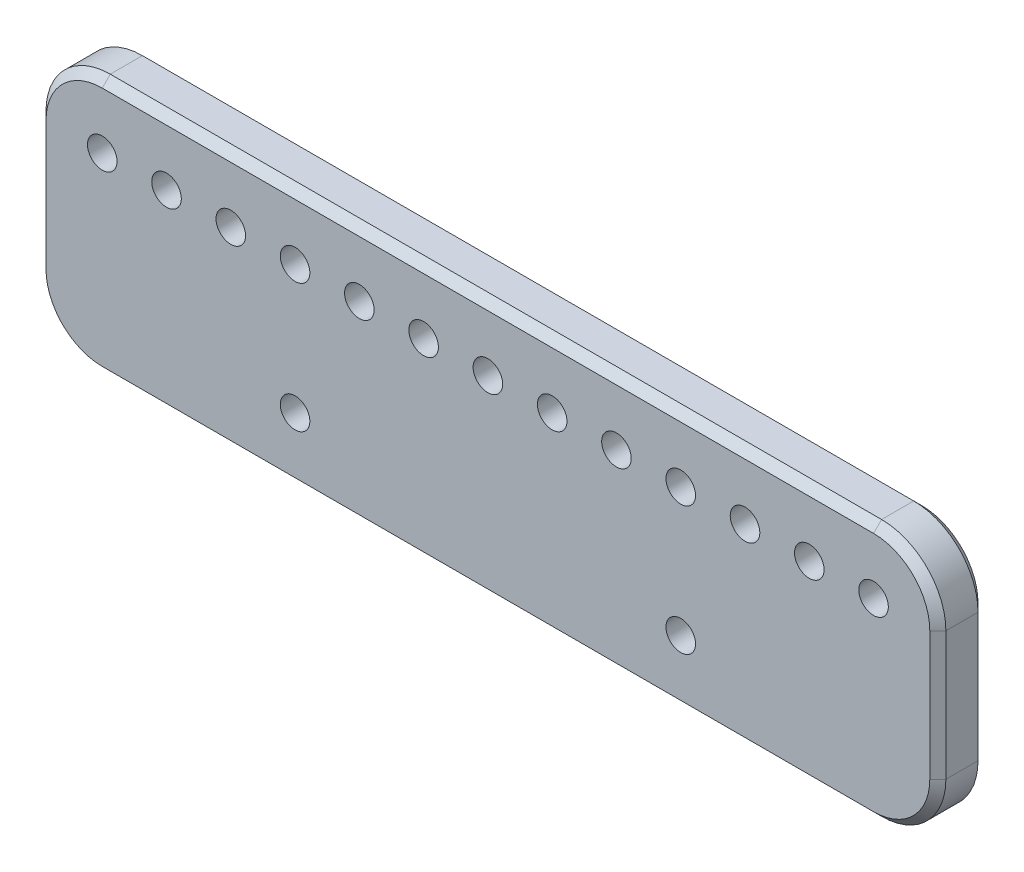
SolidWorks part; units mm, degrees
ref_plane "Front Plane" through (0, 0, 0) normal (0, 0, 1) x (1, 0, 0)
ref_plane "Top Plane" through (0, 0, 0) normal (0, 1, 0) x (1, 0, 0)
ref_plane "Right Plane" through (0, 0, 0) normal (1, 0, 0) x (0, 0, -1)
sketch "Sketch1" plane through (0, 0, 0) normal (0, 0, 1) x (1, 0, 0)
  line L0 (-3.1517, 12.7) -> (171.7055, 12.7) construction
  line L1 (0, 0) -> (177.8, 0)
  line L2 (0, 0) -> (0, 50.8)
  line L3 (0, 50.8) -> (177.8, 50.8)
  line L4 (177.8, 0) -> (177.8, 50.8)
  line L5 (88.9, 50.8) -> (88.9, 0) construction
  line L6 (-11.7976, 38.1) -> (158.7006, 38.1) construction
  circle A0 centre (50.8, 12.7) radius 2.921
  circle A2 centre (127, 12.7) radius 2.921
  circle A4 centre (12.7, 38.1) radius 2.921
  circle A5 centre (25.4, 38.1) radius 2.921
  circle A6 centre (38.1, 38.1) radius 2.921
  circle A7 centre (50.8, 38.1) radius 2.921
  circle A8 centre (63.5, 38.1) radius 2.921
  circle A9 centre (76.2, 38.1) radius 2.921
  circle A10 centre (88.9, 38.1) radius 2.921
  circle A11 centre (101.6, 38.1) radius 2.921
  circle A12 centre (114.3, 38.1) radius 2.921
  circle A13 centre (127, 38.1) radius 2.921
  circle A14 centre (139.7, 38.1) radius 2.921
  circle A15 centre (152.4, 38.1) radius 2.921
  circle A16 centre (165.1, 38.1) radius 2.921
  dimension "D3" = 5.842
  dimension "D1" = 177.8
  dimension "D2" = 50.8
  dimension "D4" = 12.7
  dimension "D5" = 38.1
  dimension "D6" = 38.1
  dimension "D7" = 12.7
  dimension "D8" = 12.7
  dimension "D9" = 13
extrude "Boss-Extrude1" add sketch "Sketch1" along normal blind 9.525
fillet "Fillet1" radius 12.7 4 edges at (0, 0, 4.7625) (0, 50.8, 4.7625) (177.8, 0, 4.7625) (177.8, 50.8, 4.7625)
chamfer "Chamfer1" distance 1.5875 angle 45 16 edges at (0, 25.4, 0) (3.7197, 3.7197, 0) (88.9, 0, 0) (3.7197, 47.0803, 0) (174.0803, 3.7197, 0) (177.8, 25.4, 0) (88.9, 50.8, 0) (174.0803, 47.0803, 0) (174.0803, 47.0803, 9.525) (177.8, 25.4, 9.525) (174.0803, 3.7197, 9.525) (88.9, 0, 9.525) (3.7197, 3.7197, 9.525) (0, 25.4, 9.525) (3.7197, 47.0803, 9.525) (88.9, 50.8, 9.525)
